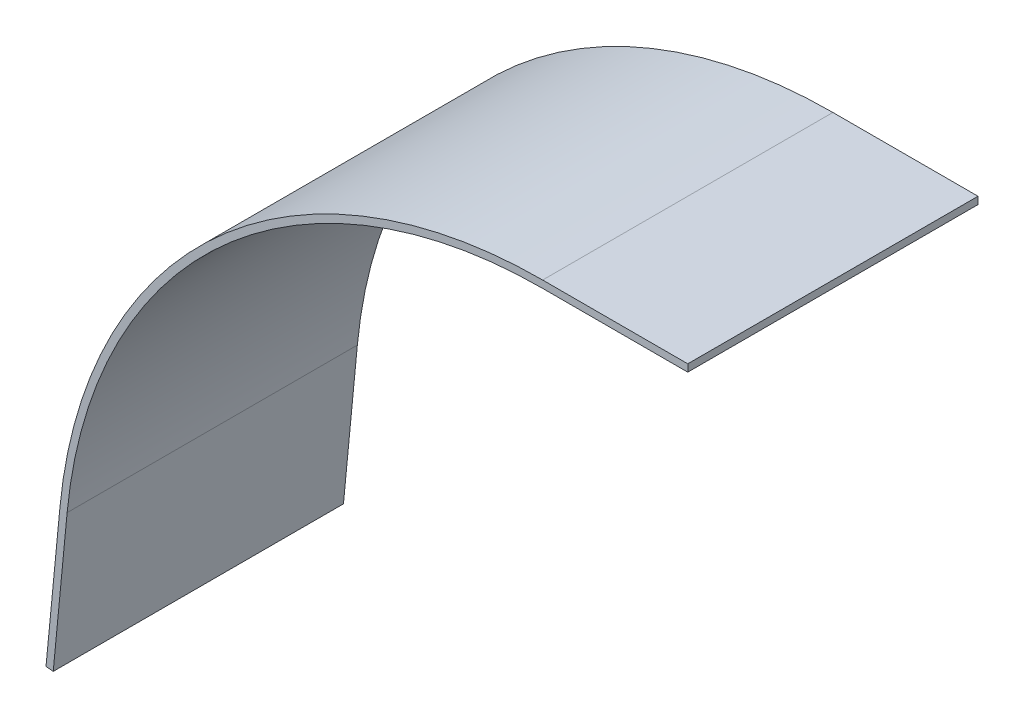
SolidWorks part; units mm, degrees
ref_plane "Front Plane" through (0, 0, 0) normal (0, 0, 1) x (1, 0, 0)
ref_plane "Top Plane" through (0, 0, 0) normal (0, 1, 0) x (1, 0, 0)
ref_plane "Right Plane" through (0, 0, 0) normal (1, 0, 0) x (0, 0, -1)
sketch "Sketch1" plane through (0, 0, 0) normal (0, 0, 1) x (1, 0, 0)
  line L0 (-34.2245, -39.9242) -> (-33.7268, -39.972)
  line L1 (-34.2245, -39.9242) -> (-33.2669, -29.9701)
  line L2 (-33.7268, -39.972) -> (-32.7692, -30.018)
  line L4 (10, -0.25) -> (10, 0.25)
  line L5 (10, -0.25) -> (0, -0.25)
  line L6 (10, 0.25) -> (0, 0.25)
  line L8 (-28.0411, -30.4729) -> (-32.7692, -30.018) construction
  arc A0 (-32.7692, -30.018) -> (0, -0.25) centre (0, -33.1705) cw
  arc A1 (0, 0.25) -> (-33.2669, -29.9701) centre (0, -33.1705) ccw
  point P14 (-31.9436, -30.2437)
  point P17 (-32.4426, -30.2123)
extrude "Boss-Extrude1" add sketch "Sketch1" against normal blind 20
